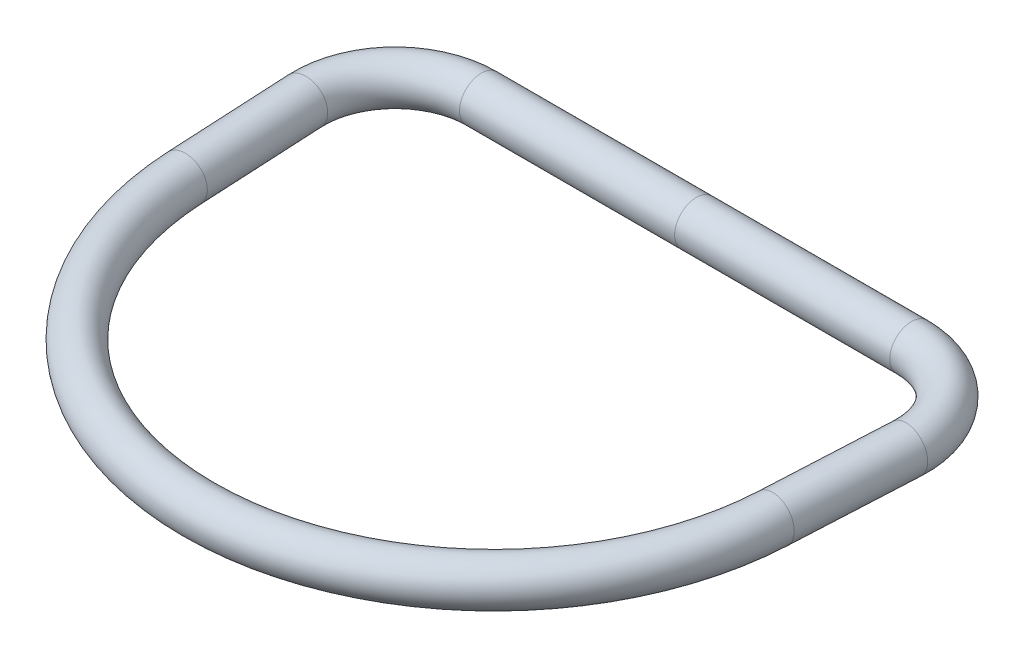
SolidWorks part; units mm, degrees
ref_plane "Front Plane" through (0, 0, 0) normal (0, 0, 1) x (1, 0, 0)
ref_plane "Top Plane" through (0, 0, 0) normal (0, 1, 0) x (1, 0, 0)
ref_plane "Right Plane" through (0, 0, 0) normal (1, 0, 0) x (0, 0, -1)
ref_plane "Plane1" through (0, -2.6401, 0) normal (0, -1, 0) x (-1, 0, 0)
sketch "Sketch1" plane through (0, -2.6401, 0) normal (0, -1, 0) x (-1, 0, 0)
  line L9 (47.1489, -14.4045) -> (48.185, 5.9121)
  line L10 (34.4254, 20.3913) -> (-34.4254, 20.3913)
  line L11 (-48.185, 5.9121) -> (-47.1489, -14.4045)
  arc A9 (48.185, 5.9121) -> (34.4254, 20.3913) centre (34.4254, 6.6138) ccw
  arc A10 (-34.4254, 20.3913) -> (-48.185, 5.9121) centre (-34.4254, 6.6138) ccw
  arc A11 (-47.1489, -14.4045) -> (47.1489, -14.4045) centre (0, -12) ccw
sketch "Sketch2" plane through (0, 0, 0) normal (1, 0, 0) x (0, 0, -1)
  circle A0 centre (20.3913, -2.6401) radius 3.4925
  dimension "D1" = 6.985
sweep "Sweep1" add profiles "Sketch2" path "Sketch1"
